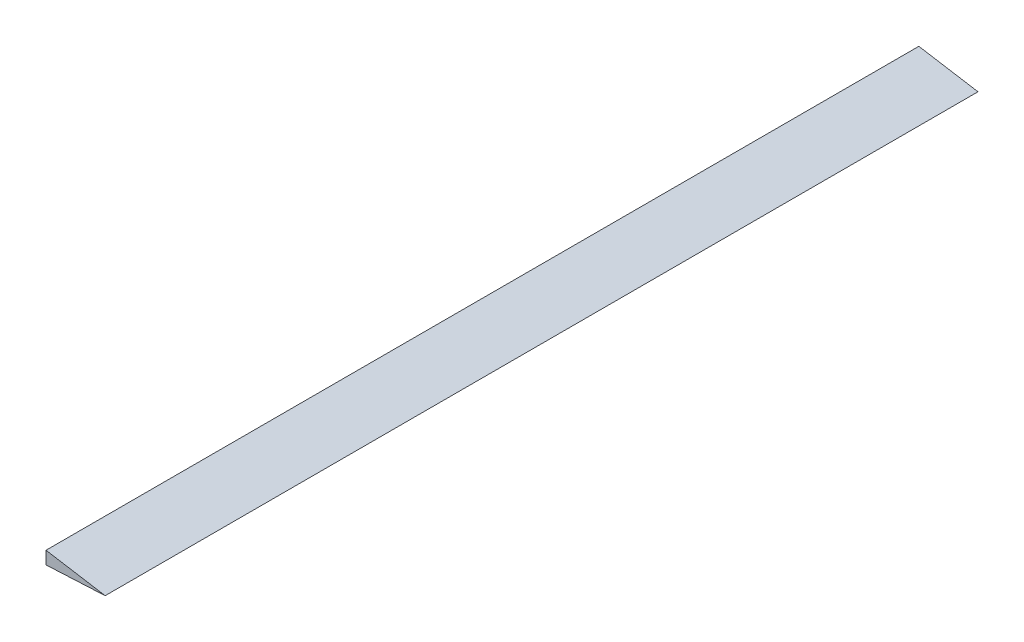
SolidWorks part; units mm, degrees
material "Balsa"
ref_plane "Front Plane" through (0, 0, 0) normal (0, 0, 1) x (1, 0, 0)
ref_plane "Top Plane" through (0, 0, 0) normal (0, 1, 0) x (1, 0, 0)
ref_plane "Right Plane" through (0, 0, 0) normal (1, 0, 0) x (0, 0, -1)
sketch "Sketch1" plane through (0, 0, 0) normal (0, 0, 1) x (1, 0, 0)
  line L0 (274.1027, -2.5258) -> (274.1027, 8.3995) construction
  line L1 (274.1027, -2.5258) -> (274.1027, 8.3995)
  line L2 (274.1027, 8.3995) -> (324.9027, 0)
  line L3 (274.1027, -2.5258) -> (324.9027, 0)
  spline S0 degree 3 poles (322.4569, 0.0391) (325.5224, -0.0392) (322.494, 0.2669) (320.1071, 0.7289) (314.4799, 1.6966) (307.762, 2.9665) (299.1562, 4.444) (289.109, 6.0546) (277.6145, 7.8586) (264.868, 9.8286) (251.0379, 11.9465) (236.3205, 14.1628) (220.9155, 16.4348) (205.0337, 18.7163) (188.8833, 20.923) (172.6824, 22.9973) (156.6226, 24.8302) (140.8504, 26.2626) (125.4788, 27.205) (110.5966, 27.6094) (96.2853, 27.4447) (82.6165, 26.7222) (69.6684, 25.4643) (57.5289, 23.7891) (46.3057, 21.7558) (36.1125, 19.4216) (27.0455, 16.847) (19.197, 14.0824) (12.6195, 11.1953) (7.3938, 8.2736) (3.4665, 5.3626) (1.0721, 2.6975) (-0.443, -0.0164) (1.1421, -2.6604) (4.365, -4.2268) (8.9712, -6.0288) (15.2436, -7.4956) (23.0321, -8.8134) (32.3248, -9.885) (43.0256, -10.722) (55.037, -11.3213) (68.2344, -11.6831) (82.4769, -11.8217) (97.6059, -11.7313) (113.4687, -11.4146) (129.93, -10.7985) (146.8597, -9.9388) (164.1026, -8.9547) (181.4553, -7.9142) (198.6946, -6.861) (215.5964, -5.837) (231.9426, -4.8635) (247.5179, -3.9672) (262.1184, -3.1571) (275.5429, -2.4457) (287.6227, -1.8357) (298.159, -1.3068) (307.1654, -0.8268) (314.174, -0.3689) (319.9998, -0.1172) (322.4569, 0.0391) (325.5224, -0.0392) (322.494, 0.2669) knots -0.015092 -0.006889 -0.001754 0 0.001748 0.006827 0.01488 0.025572 0.038694 0.054171 0.071834 0.091435 0.112685 0.135293 0.158944 0.183315 0.20807 0.232879 0.257399 0.281384 0.304706 0.327241 0.348897 0.369607 0.389308 0.407886 0.425177 0.441027 0.4553 0.467904 0.478752 0.487814 0.49509 0.500617 0.504451 0.507804 0.513091 0.520546 0.530249 0.542214 0.556382 0.572656 0.590895 0.610925 0.632536 0.655496 0.679547 0.704499 0.730211 0.756436 0.782837 0.809062 0.834776 0.859641 0.883338 0.905541 0.925965 0.944326 0.960366 0.973929 0.984908 0.993111 0.998246 1 1.001748 1.006827 1.01488 only from (324.9027, 0) to (324.9027, 0) construction
  spline S1 degree 3 poles (322.4569, 0.0391) (325.5224, -0.0392) (322.494, 0.2669) (320.1071, 0.7289) (314.4799, 1.6966) (307.762, 2.9665) (299.1562, 4.444) (289.109, 6.0546) (277.6145, 7.8586) (264.868, 9.8286) (251.0379, 11.9465) (236.3205, 14.1628) (220.9155, 16.4348) (205.0337, 18.7163) (188.8833, 20.923) (172.6824, 22.9973) (156.6226, 24.8302) (140.8504, 26.2626) (125.4788, 27.205) (110.5966, 27.6094) (96.2853, 27.4447) (82.6165, 26.7222) (69.6684, 25.4643) (57.5289, 23.7891) (46.3057, 21.7558) (36.1125, 19.4216) (27.0455, 16.847) (19.197, 14.0824) (12.6195, 11.1953) (7.3938, 8.2736) (3.4665, 5.3626) (1.0721, 2.6975) (-0.443, -0.0164) (1.1421, -2.6604) (4.365, -4.2268) (8.9712, -6.0288) (15.2436, -7.4956) (23.0321, -8.8134) (32.3248, -9.885) (43.0256, -10.722) (55.037, -11.3213) (68.2344, -11.6831) (82.4769, -11.8217) (97.6059, -11.7313) (113.4687, -11.4146) (129.93, -10.7985) (146.8597, -9.9388) (164.1026, -8.9547) (181.4553, -7.9142) (198.6946, -6.861) (215.5964, -5.837) (231.9426, -4.8635) (247.5179, -3.9672) (262.1184, -3.1571) (275.5429, -2.4457) (287.6227, -1.8357) (298.159, -1.3068) (307.1654, -0.8268) (314.174, -0.3689) (319.9998, -0.1172) (322.4569, 0.0391) (325.5224, -0.0392) (322.494, 0.2669) knots -0.015092 -0.006889 -0.001754 0 0.001748 0.006827 0.01488 0.025572 0.038694 0.054171 0.071834 0.091435 0.112685 0.135293 0.158944 0.183315 0.20807 0.232879 0.257399 0.281384 0.304706 0.327241 0.348897 0.369607 0.389308 0.407886 0.425177 0.441027 0.4553 0.467904 0.478752 0.487814 0.49509 0.500617 0.504451 0.507804 0.513091 0.520546 0.530249 0.542214 0.556382 0.572656 0.590895 0.610925 0.632536 0.655496 0.679547 0.704499 0.730211 0.756436 0.782837 0.809062 0.834776 0.859641 0.883338 0.905541 0.925965 0.944326 0.960366 0.973929 0.984908 0.993111 0.998246 1 1.001748 1.006827 1.01488 only from (324.9027, 0) to (324.9027, 0)
sketch "Sketch2" plane through (0, 0, -761.9997) normal (0, 0, -1) x (-1, 0, 0)
  line L0 (-274.1027, -2.5258) -> (-274.1027, 8.3995) construction
  line L1 (-274.1027, -2.5258) -> (-324.9027, 0) construction
  line L2 (-274.1027, 8.3995) -> (-324.9027, 0) construction
  line L3 (-274.1027, -2.5258) -> (-274.1027, 8.3995)
  line L4 (-274.1027, -2.5258) -> (-324.9027, 0)
  line L5 (-274.1027, 8.3995) -> (-324.9027, 0)
extrude "Boss-Extrude2" add sketch "Sketch2" against normal up to surface (749.2997 mm away)
